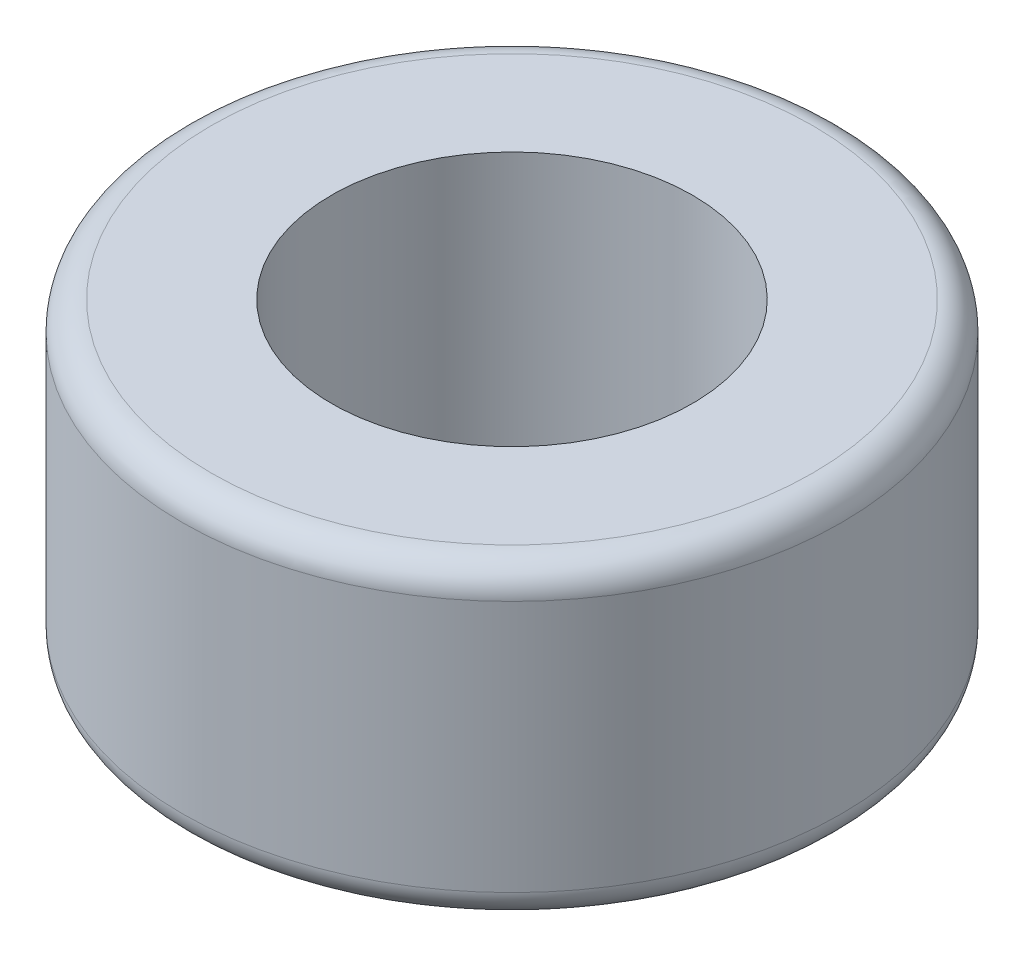
SolidWorks part; units mm, degrees
material "AISI 316 Stainless Steel Sheet (SS)"
ref_plane "Front Plane" through (0, 0, 0) normal (0, 0, 1) x (1, 0, 0)
ref_plane "Top Plane" through (0, 0, 0) normal (0, 1, 0) x (1, 0, 0)
ref_plane "Right Plane" through (0, 0, 0) normal (1, 0, 0) x (0, 0, -1)
sketch "Sketch1" plane through (0, 0, 0) normal (0, 0, 1) x (1, 0, 0)
  line L0 (0, 0) -> (0, 6.9426) construction
  line L1 (-5.75, 2.7) -> (-3.15, 2.7)
  line L2 (-5.75, 2.7) -> (-5.75, -2.7)
  line L3 (-5.75, -2.7) -> (-3.15, -2.7)
  line L4 (-3.15, 2.7) -> (-3.15, -2.7)
  point P4 (-3.15, 0)
  dimension "D1" = 5.75
  dimension "D2" = 3.15
  dimension "D3" = 5.4
revolve "Revolve1" add sketch "Sketch1" angle 360 about L0
fillet "Fillet1" radius 0.5 2 edges at (0, -2.7, -5.75) (0, 2.7, -5.75)
